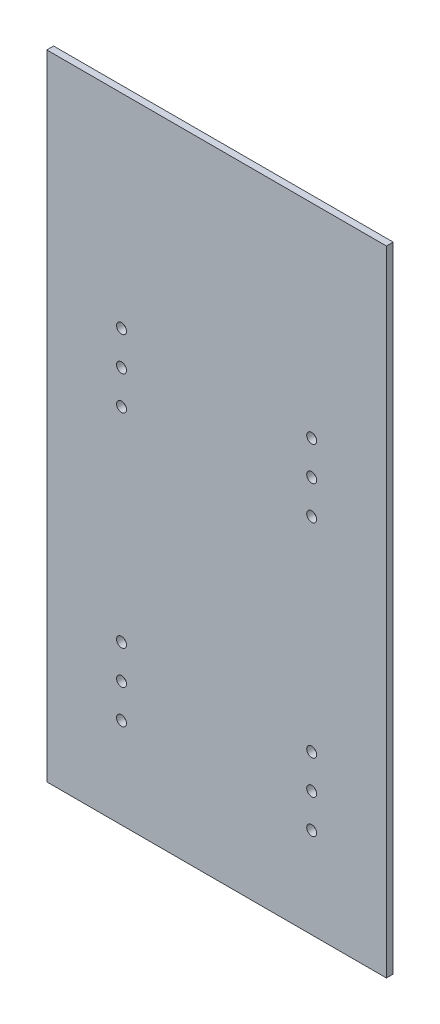
SolidWorks part; units mm, degrees
material "Thornel VCB-20 Carbon Cloth"
ref_plane "Front Plane" through (0, 0, 0) normal (0, 0, 1) x (1, 0, 0)
ref_plane "Top Plane" through (0, 0, 0) normal (0, 1, 0) x (1, 0, 0)
ref_plane "Right Plane" through (0, 0, 0) normal (1, 0, 0) x (0, 0, -1)
sketch3d "3DSketch1"
  line L1 (296.0431, 1172.6929, 0) -> (146.0431, 1172.6929, 0)
  line L2 (296.0431, 1172.6929, 0) -> (296.0431, 892.6929, 0)
  line L3 (296.0431, 892.6929, 0) -> (146.0431, 892.6929, 0)
  line L4 (146.0431, 1172.6929, 0) -> (146.0431, 892.6929, 0)
  line L5 (296.0431, 1172.6929, 0) -> (146.0431, 892.6929, 0) construction
  line L6 (296.0431, 892.6929, 0) -> (146.0431, 1172.6929, 0) construction
  point P0 (221.0431, 1032.6929, 0)
  dimension "D1" = 280
  dimension "D2" = 150
extrude "Boss-Extrude1" add sketch "3DSketch1" along a picked direction on the side of the normal blind 3
sketch3d "3DSketch2"
  circle A0 centre (179.0431, 1082.6929, 6) radius 2.2 construction
  circle A1 centre (179.0431, 1082.6929, 6) radius 2.2
  circle A2 centre (179.0431, 1067.6929, 6) radius 2.2 construction
  circle A3 centre (179.0431, 1067.6929, 6) radius 2.2
  circle A4 centre (179.0431, 1052.6929, 6) radius 2.2 construction
  circle A5 centre (179.0431, 1052.6929, 6) radius 2.2
  circle A6 centre (179.0431, 962.6929, 6) radius 2.2 construction
  circle A7 centre (179.0431, 962.6929, 6) radius 2.2
  circle A8 centre (179.0431, 947.6929, 6) radius 2.2 construction
  circle A9 centre (179.0431, 947.6929, 6) radius 2.2
  circle A10 centre (179.0431, 932.6929, 6) radius 2.2 construction
  circle A11 centre (179.0431, 932.6929, 6) radius 2.2
  circle A12 centre (263.0431, 932.6929, 6) radius 2.2 construction
  circle A13 centre (263.0431, 932.6929, 6) radius 2.2
  circle A14 centre (263.0431, 947.6929, 6) radius 2.2 construction
  circle A15 centre (263.0431, 947.6929, 6) radius 2.2
  circle A16 centre (263.0431, 962.6929, 6) radius 2.2 construction
  circle A17 centre (263.0431, 962.6929, 6) radius 2.2
  circle A18 centre (263.0431, 1052.6929, 6) radius 2.2 construction
  circle A19 centre (263.0431, 1052.6929, 6) radius 2.2
  circle A20 centre (263.0431, 1082.6929, 6) radius 2.2 construction
  circle A21 centre (263.0431, 1082.6929, 6) radius 2.2
  circle A22 centre (263.0431, 1067.6929, 6) radius 2.2 construction
  circle A23 centre (263.0431, 1067.6929, 6) radius 2.2
  point P2 (179.0431, 1082.6929, 3.8)
  point P4 (179.0431, 1082.6929, 3.8)
  point P7 (179.0431, 1067.6929, 3.8)
  point P9 (179.0431, 1067.6929, 3.8)
  point P12 (179.0431, 1052.6929, 3.8)
  point P14 (179.0431, 1052.6929, 3.8)
  point P17 (179.0431, 962.6929, 3.8)
  point P19 (179.0431, 962.6929, 3.8)
  point P22 (179.0431, 947.6929, 3.8)
  point P24 (179.0431, 947.6929, 3.8)
  point P27 (179.0431, 932.6929, 3.8)
  point P29 (179.0431, 932.6929, 3.8)
  point P32 (263.0431, 932.6929, 3.8)
  point P34 (263.0431, 932.6929, 3.8)
  point P37 (263.0431, 947.6929, 3.8)
  point P39 (263.0431, 947.6929, 3.8)
  point P42 (263.0431, 962.6929, 3.8)
  point P44 (263.0431, 962.6929, 3.8)
  point P47 (263.0431, 1052.6929, 3.8)
  point P49 (263.0431, 1052.6929, 3.8)
  point P52 (263.0431, 1082.6929, 3.8)
  point P54 (263.0431, 1082.6929, 3.8)
  point P57 (263.0431, 1067.6929, 3.8)
  point P59 (263.0431, 1067.6929, 3.8)
extrude "Cut-Extrude1" cut sketch "3DSketch2" along a picked direction on the side of the normal blind 18 contours A19 | A23 | A21 | A1 | A3 | A5 | A7 | A9 | A11 | A13 | A15 | A17
